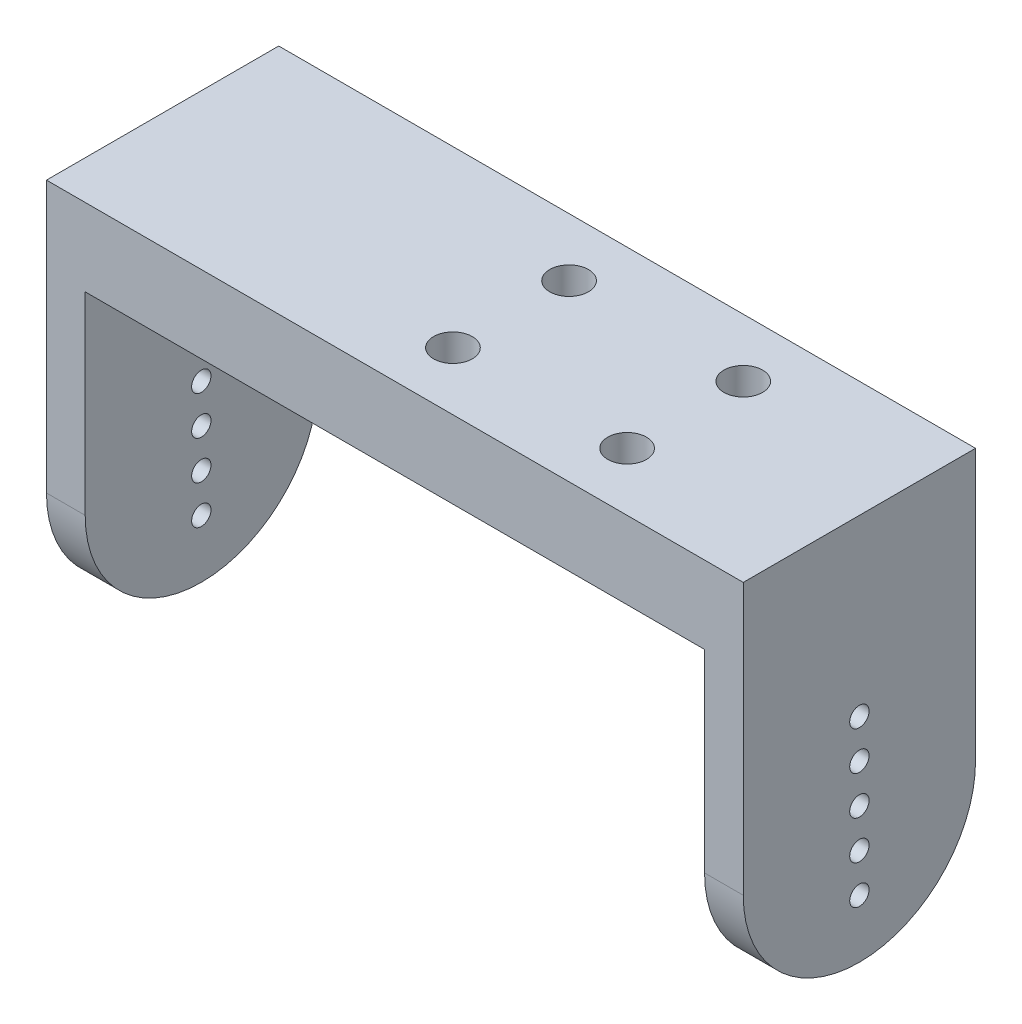
SolidWorks part; units mm, degrees
ref_plane "Front Plane" through (0, 0, 0) normal (0, 0, 1) x (1, 0, 0)
ref_plane "Top Plane" through (0, 0, 0) normal (0, 1, 0) x (1, 0, 0)
ref_plane "Right Plane" through (0, 0, 0) normal (1, 0, 0) x (0, 0, -1)
sketch "Sketch1" plane through (0, 0, 0) normal (0, 0, 1) x (1, 0, 0)
  line L1 (-18, 10) -> (18, 10)
  line L2 (-18, 10) -> (-18, -10)
  line L3 (-18, -10) -> (18, -10)
  line L4 (18, 10) -> (18, -10)
  line L5 (-18, 10) -> (18, -10) construction
  line L6 (-18, -10) -> (18, 10) construction
  point P0 (0, 0)
  dimension "D1" = 20
  dimension "D2" = 36
extrude "Boss-Extrude1" add sketch "Sketch1" along normal blind 12
sketch "Sketch2" plane through (18, 0, 0) normal (1, 0, 0) x (0, 0, -1)
  line L4 (0, -10) -> (0, 10)
  line L5 (0, 10) -> (-12, 10)
  line L6 (-12, 10) -> (-12, -10)
  line L7 (-12, -10) -> (0, -10)
  line L8 (0, -4) -> (0, 10)
  line L9 (0, 10) -> (-12, 10)
  line L10 (-12, 10) -> (-12, -4)
  arc A0 (-12, -4) -> (0, -4) centre (-6, -4) ccw
  line M1 (0, -10) -> (0, 10)
  line M3 (-12, 10) -> (-12, -10)
  line M4 (-12, -10) -> (0, -10)
  dimension "D1" = 0
sketch "Sketch3" plane through (0, 0, 12) normal (0, 0, 1) x (1, 0, 0)
  line L0 (-16, 8) -> (-16, -8)
  line L1 (-16, -8) -> (16, -8)
  line L2 (16, -8) -> (16, 8)
  line L3 (16, 8) -> (-16, 8)
  line L4 (18, -10) -> (18, 10)
  line L5 (18, 10) -> (-18, 10)
  line L6 (-18, 10) -> (-18, -10)
  line L7 (-18, -10) -> (18, -10)
  line L8 (18, -10) -> (18, 10)
  line L9 (18, 10) -> (-18, 10)
  line L10 (-18, 10) -> (-18, -10)
  line L11 (-18, -10) -> (18, -10)
  dimension "D1" = 0
  dimension "D2" = 2
extrude "Cut-Extrude1" cut sketch "Sketch3" against normal blind 12 contours L2 L3 L0 L1
sketch "Sketch4" plane through (0, -8, 0) normal (0, 1, 0) x (1, 0, 0)
  line L0 (16, 0) -> (16, -12) construction
  line L1 (-16, 0) -> (16, 0)
  line L2 (-16, 0) -> (-16, -12)
  line L3 (-16, -12) -> (16, -12)
  line L4 (16, 0) -> (16, -12)
extrude "Cut-Extrude2" cut sketch "Sketch4" against normal blind 12
extrude "Cut-Extrude3" cut sketch "Sketch2" against normal through all contours A0 M3 M4 | A0 M4 M1
sketch "Sketch5" plane through (0, 10, 0) normal (0, 1, 0) x (1, 0, 0)
  line L0 (18, -6) -> (-18, -6) construction
  line L1 (18, -12) -> (18, 0) construction
  line L2 (-18, -12) -> (-18, 0) construction
  circle A0 centre (9, -3) radius 1
  circle A1 centre (9, -9) radius 1
  circle A2 centre (0, -9) radius 1
  circle A3 centre (0, -3) radius 1
  dimension "D1" = 9
  dimension "D2" = 3
  dimension "D3" = 2
extrude "Cut-Extrude4" cut sketch "Sketch5" against normal blind 10 contours A0 | A3 | A2 | A1
sketch "Sketch6" plane through (18, 0, 0) normal (1, 0, 0) x (0, 0, -1)
  circle A0 centre (-6, -7) radius 0.5
  arc A1 (-12, -4) -> (0, -4) centre (-6, -4) ccw construction
  circle A2 centre (-6, -5) radius 0.5
  circle A3 centre (-6, -3) radius 0.5
  circle A4 centre (-6, -1) radius 0.5
  circle A5 centre (-6, 1) radius 0.5
  point P5 (-6, -10)
  dimension "D1" = 3
  dimension "D2" = 5
extrude "Cut-Extrude5" cut sketch "Sketch6" against normal through all
sketch "Sketch7" plane through (0, 8, 0) normal (0, -1, 0) x (1, 0, 0)
  line L0 (16, 0) -> (16, 12) construction
  line L1 (-16, 12) -> (16, 12)
  line L2 (-16, 12) -> (-16, 11)
  line L3 (-16, 11) -> (16, 11)
  line L4 (16, 12) -> (16, 11)
  line L5 (-16, 0) -> (-16, 12) construction
  line L6 (-16, 1) -> (16, 1)
  line L7 (-16, 1) -> (-16, 0)
  line L8 (-16, 0) -> (16, 0)
  line L9 (16, 1) -> (16, 0)
  dimension "D1" = 1
  dimension "D2" = 1
extrude "Boss-Extrude2" add sketch "Sketch7" along normal blind 2
